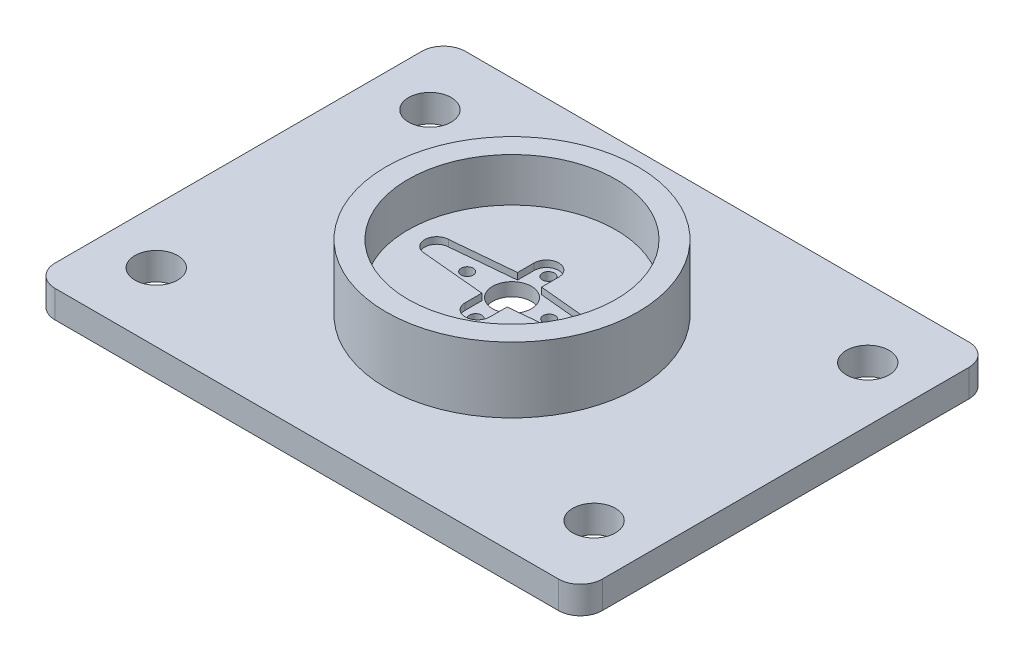
SolidWorks part; units mm, degrees
ref_plane "Plan de face" through (0, 0, 0) normal (0, 0, 1) x (1, 0, 0)
ref_plane "Plan de dessus" through (0, 0, 0) normal (0, 1, 0) x (1, 0, 0)
ref_plane "Plan de droite" through (0, 0, 0) normal (1, 0, 0) x (0, 0, -1)
sketch "Esquisse1" plane through (0, 0, 0) normal (0, 1, 0) x (1, 0, 0)
  line L0 (0, 0) -> (50, 0) construction
  line L1 (-50, 37.5) -> (50, 37.5)
  line L2 (-50, 37.5) -> (-50, -37.5)
  line L3 (-50, -37.5) -> (50, -37.5)
  line L4 (50, 37.5) -> (50, -37.5)
  line L5 (0, 0) -> (0, -37.5) construction
  circle A0 centre (-40, 25) radius 3.9
  circle A1 centre (-40, -25) radius 3.9
  circle A2 centre (40, -25) radius 3.9
  circle A3 centre (40, 25) radius 3.9
  arc A4 (-46, 37.5) -> (-50, 33.5) centre (-46, 33.5) ccw
  arc A5 (46, 37.5) -> (50, 33.5) centre (46, 33.5) cw
  arc A6 (-46, -37.5) -> (-50, -33.5) centre (-46, -33.5) cw
  arc A7 (46, -37.5) -> (50, -33.5) centre (46, -33.5) ccw
  point P4 (0, 37.5)
  point P6 (50, 0)
  point P20 (-50, 33.5)
  dimension "D3" = 7.8
  dimension "D6" = 4
  dimension "D1" = 100
  dimension "D2" = 75
  dimension "D4" = 10
  dimension "D5" = 12.5
extrude "Boss.-Extru.1" add sketch "Esquisse1" along normal blind 5 contours L3 A7 L4 A5 L1 A4 L2 A6 A1 A0 A2 A3
sketch "Esquisse2" plane through (0, 5, 0) normal (0, 1, 0) x (1, 0, 0)
  circle A0 centre (0, 0) radius 23
  circle A1 centre (0, 0) radius 19
  dimension "D1" = 38
  dimension "D2" = 4
extrude "Boss.-Extru.2" add sketch "Esquisse2" along normal blind 12
sketch "Esquisse5" plane through (0, 5, 0) normal (0, 1, 0) x (1, 0, 0)
  circle A1 centre (0, 0) radius 19
  circle A2 centre (0, 0) radius 19
  dimension "D1" = 0
extrude "Boss.-Extru.3" add sketch "Esquisse5" along normal blind 4
sketch "Esquisse8" plane through (0, 9, 0) normal (0, 1, 0) x (1, 0, 0)
  line L0 (0.1357, 3.3473) -> (16.35, 1.8)
  line L1 (0.1357, -3.3473) -> (16.35, -1.8)
  line L2 (-3.35, 0) -> (18.15, 0) construction
  line L3 (0, 0) -> (0, -3.35) construction
  line L4 (-1.85, -6.3) -> (1.85, -6.3)
  line L5 (-1.85, 0) -> (1.85, 0)
  line L6 (-1.85, -6.3) -> (-1.85, 6.3)
  line L7 (-1.85, 6.3) -> (1.85, 6.3)
  line L8 (1.85, -6.3) -> (1.85, 6.3)
  line L9 (-1.85, 2.9) -> (-1.85, -2.9) construction
  line L10 (-1.85, 2.9) -> (-13.75, 1.8)
  line L11 (-13.75, -1.8) -> (-1.85, -2.9)
  line L12 (-1.8868, 3.2983) -> (-13.7694, 2.1999)
  line L13 (-13.7694, -2.1999) -> (-1.8868, -3.2983)
  line L14 (-1.45, -6.3) -> (-1.45, 6.3)
  line L15 (2.25, -6.3) -> (2.25, 6.3)
  line L16 (0.0977, 2.9491) -> (16.3322, 1.3999)
  line L17 (0.0977, -2.9491) -> (16.3322, -1.3999)
  line L18 (-2.25, 6.3) -> (-2.25, 3.2647)
  line L19 (2.25, 6.3) -> (2.25, -6.3)
  line L20 (-2.25, -6.3) -> (-2.25, -3.2647)
  circle A0 centre (0, 0) radius 19 construction
  circle A1 centre (0, 0) radius 19
  arc A2 (0.1357, 3.3473) -> (-0.1357, 3.3473) centre (0, 0) ccw
  arc A3 (16.35, -1.8) -> (16.35, 1.8) centre (16.35, 0) ccw
  circle A4 centre (0, 0) radius 1.1
  arc A5 (-0.1357, 3.3473) -> (0.1357, 3.3473) centre (0, 0) cw
  arc A6 (-0.1357, -3.3473) -> (0.1357, -3.3473) centre (0, 0) ccw
  arc A7 (0.1357, -3.3473) -> (-0.1357, -3.3473) centre (0, 0) cw
  arc A8 (1.85, 6.3) -> (-1.85, 6.3) centre (0, 6.3) ccw
  arc A9 (1.85, -6.3) -> (-1.85, -6.3) centre (0, -6.3) cw
  arc A10 (-13.75, 1.8) -> (-13.75, -1.8) centre (-13.75, 0) ccw
  arc A11 (-13.7694, 2.1999) -> (-13.7694, -2.1999) centre (-13.75, 0) ccw
  arc A12 (1.45, -6.3) -> (-1.45, -6.3) centre (0, -6.3) cw
  arc A13 (2.25, 6.3) -> (-2.25, 6.3) centre (0, 6.3) ccw
  arc A14 (16.3322, -1.3999) -> (16.3322, 1.3999) centre (16.35, 0) ccw
  arc A15 (2.25, -6.3) -> (-2.25, -6.3) centre (0, -6.3) cw
  point P5 (0, 3.35)
  point P6 (16.35, 1.8)
  point P11 (-3.35, 0)
  point P12 (18.15, 0)
  point P20 (-15.55, 0)
  point P29 (0, 0)
  point P36 (0, 8.15)
  point P37 (0, -8.15)
  point P38 (-1.85, 0)
  dimension "D1" = 6.7
  dimension "D2" = 3.6
  dimension "D3" = 2.2
  dimension "D6" = 3.6
  dimension "D4" = 3.7
  dimension "D5" = 16.3
  dimension "D7" = 33.7
  dimension "D8" = 21.5
  dimension "D9" = 5.8
  dimension "D10" = 5.451
  dimension "D11" = 0.4
extrude "Enlèv. mat.-Extru.4" cut sketch "Esquisse8" against normal blind 1.2
sketch "Esquisse9" plane through (0, 7.8, 0) normal (0, 1, 0) x (1, 0, 0)
  line L8 (2.25, -6.3) -> (2.25, -3.1455)
  line L9 (2.25, -3.1455) -> (16.35, -1.8)
  line L10 (16.35, 1.8) -> (2.25, 3.1455)
  line L11 (2.25, 3.1455) -> (2.25, 6.3)
  line L12 (-2.25, 6.3) -> (-2.25, 3.2647)
  line L13 (-2.25, 3.2647) -> (-13.7694, 2.1999)
  line L14 (-13.7694, -2.1999) -> (-2.25, -3.2647)
  line L15 (-2.25, -3.2647) -> (-2.25, -6.3)
  line L16 (2.25, -6.3) -> (2.25, -3.1455)
  line L17 (2.25, -3.1455) -> (16.35, -1.8)
  line L18 (16.35, 1.8) -> (2.25, 3.1455)
  line L19 (2.25, 3.1455) -> (2.25, 6.3)
  line L20 (-2.25, 6.3) -> (-2.25, 3.2647)
  line L21 (-2.25, 3.2647) -> (-13.7694, 2.1999)
  line L22 (-13.7694, -2.1999) -> (-2.25, -3.2647)
  line L23 (-2.25, -3.2647) -> (-2.25, -6.3)
  circle A0 centre (0, 0) radius 3.55
  arc A4 (16.35, -1.8) -> (16.35, 1.8) centre (16.35, 0) ccw
  arc A5 (2.25, 6.3) -> (-2.25, 6.3) centre (0, 6.3) ccw
  arc A6 (-13.7694, 2.1999) -> (-13.7694, -2.1999) centre (-13.75, 0) ccw
  arc A7 (-2.25, -6.3) -> (2.25, -6.3) centre (0, -6.3) ccw
  arc A8 (16.35, -1.8) -> (16.35, 1.8) centre (16.35, 0) ccw
  arc A9 (2.25, 6.3) -> (-2.25, 6.3) centre (0, 6.3) ccw
  arc A10 (-13.7694, 2.1999) -> (-13.7694, -2.1999) centre (-13.75, 0) ccw
  arc A11 (-2.25, -6.3) -> (2.25, -6.3) centre (0, -6.3) ccw
  dimension "D2" = 7.1
  dimension "D1" = 0
extrude "Enlèv. mat.-Extru.5" cut sketch "Esquisse9" against normal through all contours A0
sketch "Esquisse6" plane through (0, 0, 0) normal (0, -1, 0) x (1, 0, 0)
  circle A1 centre (0, 0) radius 19
  circle A2 centre (0, 0) radius 19
  dimension "D1" = 0
extrude "Enlèv. mat.-Extru.3" cut sketch "Esquisse6" against normal offset from surface (5.4 mm away) 2.4 up to face at (0, 7.8, 3.55)
sketch "Esquisse10" plane through (0, 7.8, 0) normal (0, 1, 0) x (1, 0, 0)
  line L1 (0, 0) -> (0, -3.35) construction
  line L2 (16.55, 0) -> (18.15, 0) construction
  line L3 (-13.95, 0) -> (-12.03, 0) construction
  line L4 (-12.03, 0) -> (-10.11, 0) construction
  line L5 (-10.11, 0) -> (-8.19, 0) construction
  line L6 (-8.19, 0) -> (-6.27, 0) construction
  line L7 (-6.27, 0) -> (-4.35, 0) construction
  line L8 (2.25, -6.3) -> (2.25, -3.1455)
  line L9 (2.25, -3.1455) -> (16.35, -1.8)
  line L10 (16.35, 1.8) -> (2.25, 3.1455)
  line L11 (2.25, 3.1455) -> (2.25, 6.3)
  line L12 (-2.25, 6.3) -> (-2.25, 3.2647)
  line L13 (-2.25, 3.2647) -> (-13.7694, 2.1999)
  line L14 (-13.7694, -2.1999) -> (-2.25, -3.2647)
  line L15 (-2.25, -3.2647) -> (-2.25, -6.3)
  line L16 (2.25, -6.3) -> (2.25, -3.1455)
  line L17 (2.25, -3.1455) -> (16.35, -1.8)
  line L18 (16.35, 1.8) -> (2.25, 3.1455)
  line L19 (2.25, 3.1455) -> (2.25, 6.3)
  line L20 (-2.25, 6.3) -> (-2.25, 3.2647)
  line L21 (-2.25, 3.2647) -> (-13.7694, 2.1999)
  line L22 (-13.7694, -2.1999) -> (-2.25, -3.2647)
  line L23 (-2.25, -3.2647) -> (-2.25, -6.3)
  line L24 (4.85, 0) -> (6.8, 0) construction
  line L25 (6.8, 0) -> (8.75, 0) construction
  line L26 (8.75, 0) -> (10.7, 0) construction
  line L27 (10.7, 0) -> (12.65, 0) construction
  line L28 (12.65, 0) -> (14.6, 0) construction
  line L29 (14.6, 0) -> (16.55, 0) construction
  line L30 (0, 6.65) -> (0, 4.35) construction
  line L31 (0, -4.35) -> (0, -6.65) construction
  circle A0 centre (0, 4.35) radius 0.5
  circle A1 centre (0, 6.65) radius 0.5
  circle A2 centre (4.85, 0) radius 0.5
  circle A3 centre (0, 0) radius 3.35
  arc A4 (16.35, -1.8) -> (16.35, 1.8) centre (16.35, 0) ccw
  arc A5 (2.25, 6.3) -> (-2.25, 6.3) centre (0, 6.3) ccw
  arc A6 (-13.7694, 2.1999) -> (-13.7694, -2.1999) centre (-13.75, 0) ccw
  arc A7 (-2.25, -6.3) -> (2.25, -6.3) centre (0, -6.3) ccw
  arc A8 (16.35, -1.8) -> (16.35, 1.8) centre (16.35, 0) ccw
  arc A9 (2.25, 6.3) -> (-2.25, 6.3) centre (0, 6.3) ccw
  arc A10 (-13.7694, 2.1999) -> (-13.7694, -2.1999) centre (-13.75, 0) ccw
  arc A11 (-2.25, -6.3) -> (2.25, -6.3) centre (0, -6.3) ccw
  circle A12 centre (6.8, 0) radius 0.5
  circle A13 centre (8.75, 0) radius 0.5
  circle A14 centre (10.7, 0) radius 0.5
  circle A15 centre (12.65, 0) radius 0.5
  circle A16 centre (14.6, 0) radius 0.5
  circle A17 centre (16.55, 0) radius 0.5
  circle A18 centre (0, -6.65) radius 0.5
  circle A19 centre (0, -4.35) radius 0.5
  circle A20 centre (-4.35, 0) radius 0.5
  circle A21 centre (-6.27, 0) radius 0.5
  circle A22 centre (-8.19, 0) radius 0.5
  circle A23 centre (-10.11, 0) radius 0.5
  circle A24 centre (-12.03, 0) radius 0.5
  circle A25 centre (-13.95, 0) radius 0.5
  circle A26 centre (6.8, 0) radius 1.1
  circle A27 centre (12.65, 0) radius 1.1
  circle A28 centre (-8.19, 0) radius 1.1
  circle A29 centre (0, 6.65) radius 1.1
  circle A30 centre (0, -6.65) radius 1.1
  point P12 (16.55, 0)
  point P19 (3.35, 0)
  point P21 (0, 3.35)
  point P49 (-3.35, 0)
  point P50 (-15.5498, -0.0279)
  point P51 (0, 8.15)
  point P60 (0, -7.2778)
  dimension "D3" = 1
  dimension "D9" = 6.7
  dimension "D10" = 1.92
  dimension "D14" = 2.2
  dimension "D2" = 1.6
  dimension "D4" = 1
  dimension "D5" = 1.5
  dimension "D6" = 1.5
  dimension "D7" = 1
  dimension "D8" = 1.6
  dimension "D11" = 2.3
  dimension "D12" = 1.95
  dimension "D13" = 1
  dimension "D1" = 0
extrude "Enlèv. mat.-Extru.6" cut sketch "Esquisse10" against normal through all contours A29 A1 | A1 | A18 | A30 A18 | A28 A22 | A22 | A26 A12 | A12 | A27 A15 | A15
